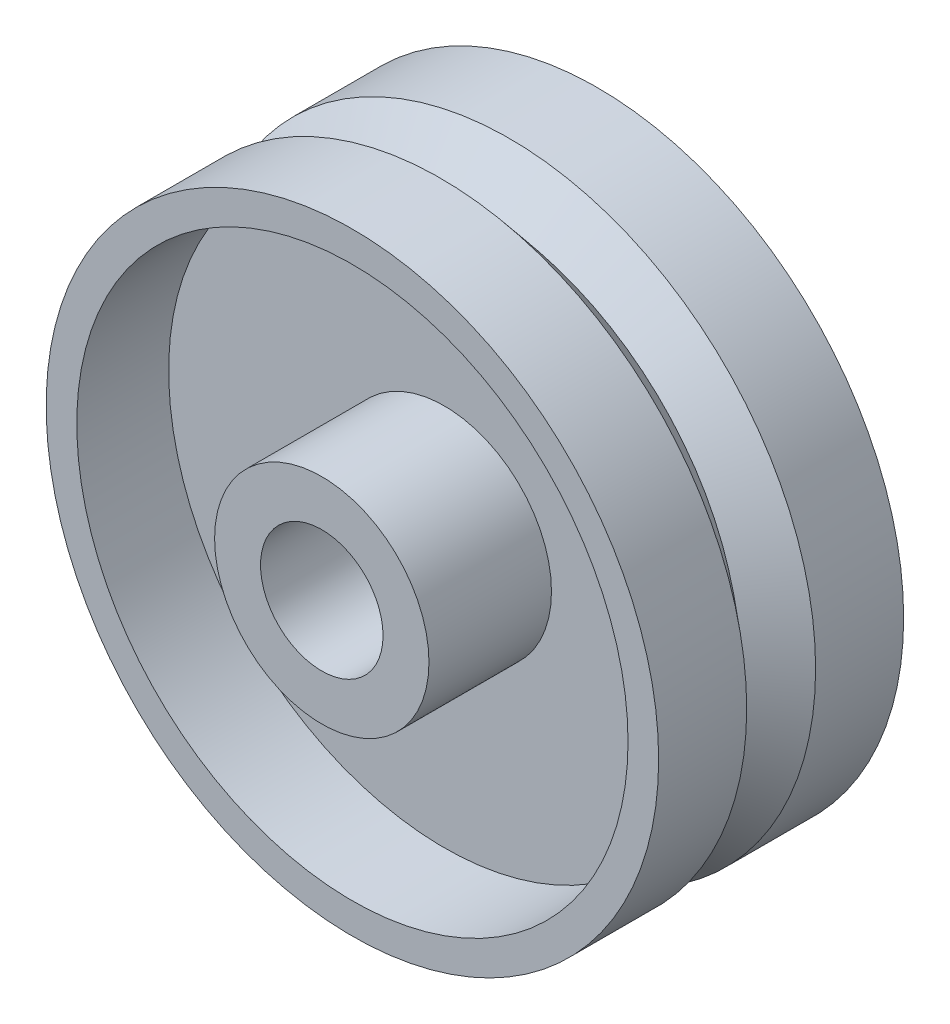
SolidWorks part; units mm, degrees
material "AISI 304"
ref_plane "Front Plane" through (0, 0, 0) normal (0, 0, 1) x (1, 0, 0)
ref_plane "Top Plane" through (0, 0, 0) normal (0, 1, 0) x (1, 0, 0)
ref_plane "Right Plane" through (0, 0, 0) normal (1, 0, 0) x (0, 0, -1)
sketch "Croquis1" plane through (0, 0, 0) normal (1, 0, 0) x (0, 0, -1)
  line L0 (0, 0) -> (43.7442, 0) construction
  line L1 (25, 10) -> (-25, 10)
  line L2 (-25, 10) -> (-25, 17.5)
  line L3 (-25, 17.5) -> (-5, 17.5)
  line L4 (-5, 17.5) -> (-5, 45)
  line L5 (-5, 45) -> (-20, 45)
  line L6 (-20, 45) -> (-20, 50)
  line L7 (-20, 50) -> (-5.6252, 50)
  line L8 (20, 50) -> (20, 45)
  line L9 (20, 45) -> (5, 45)
  line L10 (5, 45) -> (5, 17.5)
  line L11 (5, 17.5) -> (25, 17.5)
  line L12 (25, 17.5) -> (25, 10)
  line L13 (0, 43.2961) -> (0, 10) construction
  line L14 (0, 43.2961) -> (-5.6252, 50)
  line L15 (0, 43.2961) -> (5.6252, 50)
  line L16 (5.6252, 50) -> (20, 50)
  point P6 (0, 10)
  dimension "D1" = 40
  dimension "D2" = 7.5
  dimension "D3" = 10
  dimension "D4" = 5
  dimension "D5" = 35
  dimension "D6" = 20
  dimension "D7" = 20
  dimension "D8" = 20
  dimension "D9" = 15
  dimension "D10" = 15
  dimension "D11" = 100
  dimension "D12" = 40
  dimension "D13" = 40
revolve "Revolución1" add sketch "Croquis1" angle 360 about L0
